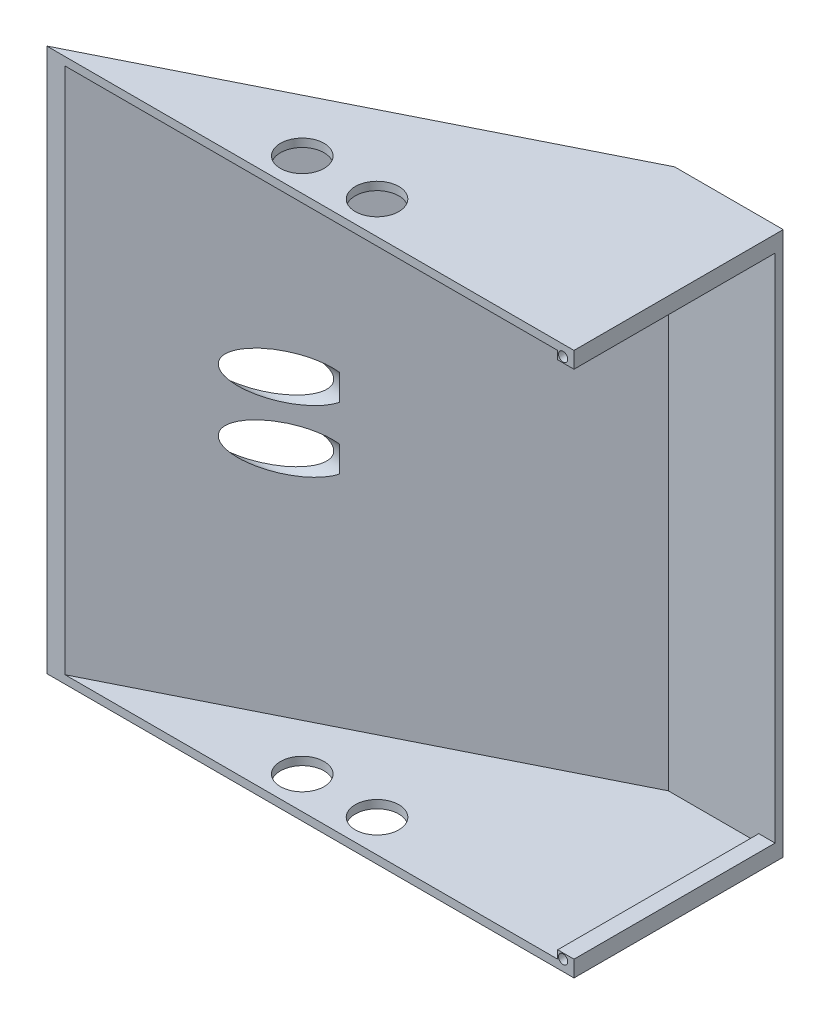
SolidWorks part; units mm, degrees
ref_plane "Alzado" through (0, 0, 0) normal (0, 0, 1) x (1, 0, 0)
ref_plane "Planta" through (0, 0, 0) normal (0, 1, 0) x (1, 0, 0)
ref_plane "Vista lateral" through (0, 0, 0) normal (1, 0, 0) x (0, 0, -1)
sketch "Croquis1" plane through (0, 0, 0) normal (0, 1, 0) x (1, 0, 0)
  line L0 (0, 0) -> (200, 0)
  line L5 (200, 0) -> (200, 80)
  line L6 (200, 80) -> (160, 80)
  line L7 (160, 80) -> (0, 0)
  dimension "D1" = 200
  dimension "D2" = 80
  dimension "D3" = 40
extrude "Saliente-Extruir2" add sketch "Croquis1" along normal blind 200
sketch "Croquis2" plane through (0, 200, 0) normal (0, 1, 0) x (1, 0, 0)
  line L0 (0, 0) -> (200, 0) construction
  circle A0 centre (88.0116, 15) radius 8.02
  circle A1 centre (115.5316, 15) radius 8.02
  dimension "D2" = 16.04
  dimension "D3" = 15
  dimension "D4" = 16.04
  dimension "D1" = 15
  dimension "D5" = 27.52
sketch "Croquis3" plane through (0, 0, -80) normal (0, 0, -1) x (-1, 0, 0)
  line L0 (-200, 0) -> (-200, 200) construction
sketch "Croquis5" plane through (0, 0, 0) normal (0, -1, 0) x (1, 0, 0)
  circle A0 centre (88.0116, -15) radius 8.02
  circle A1 centre (115.5316, -15) radius 8.02
ref_plane "Plano1" through (0, 0, 0) normal (1, 0, 0) x (0, 0, -1)
shell "Vaciado2" thickness 3
sketch "Croquis6" plane through (0, 0, 0) normal (1, 0, 0) x (0, 0, -1)
  line L1 (0, 200) -> (0, 0) construction
  line L3 (30, 88.575) -> (30, 111.425) construction
  line L4 (80, 0) -> (0, 0) construction
  circle A0 centre (30, 88.575) radius 8.2
  circle A1 centre (30, 111.425) radius 8.2
  point P2 (30, 100)
  dimension "D1" = 16.4
  dimension "D2" = 22.85
  dimension "D3" = 30
  dimension "D4" = 16.4
  dimension "D6" = 30
  dimension "D5" = 100
extrude "Cortar-Extruir4" cut sketch "Croquis6" along normal blind 80 contours A1 | A0
extrude "Cortar-Extruir5" cut sketch "Croquis2" against normal blind 3 contours A0 | A1
extrude "Cortar-Extruir6" cut sketch "Croquis5" against normal blind 3 contours A0 | A1
sketch "Croquis7" plane through (0, 0, 0) normal (0, 0, 1) x (1, 0, 0)
  line L0 (0, 0) -> (200, 0) construction
  line L1 (15, 10) -> (22.4, 10)
  line L2 (15, 10) -> (15, 17.4)
  line L3 (15, 17.4) -> (22.4, 17.4)
  line L4 (22.4, 10) -> (22.4, 17.4)
  line L5 (0, -44) -> (0, 44) construction
  point P4 (18.7, 10)
  dimension "D1" = 7.4
  dimension "D2" = 7.4
  dimension "D3" = 10
  dimension "D4" = 15
ref_plane "Plano2" through (0, 100, 0) normal (0, 1, 0) x (1, 0, 0)
extrude "Cortar-Extruir11" cut sketch "Croquis7" against normal blind 3 contours L4 L3 L2 L1
mirror "Simetría5" about plane through (0, 100, 0) normal (0, 1, 0) of "Cortar-Extruir11"
sketch "Croquis8" plane through (0, 0, 0) normal (0, 0, 1) x (1, 0, 0)
  line L0 (0, 200) -> (200, 200) construction
  line L1 (22.04, 103.52) -> (15, 103.52)
  line L2 (22.04, 103.52) -> (22.04, 96.48)
  line L3 (22.04, 96.48) -> (15, 96.48)
  line L4 (15, 103.52) -> (15, 96.48)
  line L5 (0, 0) -> (200, 0) construction
  line L7 (0, -44) -> (0, 44) construction
  point P6 (18.52, 103.52)
  point P9 (18.52, 96.48)
  dimension "D1" = 96.48
  dimension "D2" = 96.48
  dimension "D3" = 3.52
  dimension "D4" = 15
extrude "Cortar-Extruir12" cut sketch "Croquis8" against normal blind 3
sketch "Croquis9" plane through (0, 0, 0) normal (0, 0, 1) x (1, 0, 0)
  line L0 (200, 0) -> (200, 200) construction
  line L1 (192, 192) -> (157, 192)
  line L2 (192, 192) -> (192, 157)
  line L3 (192, 157) -> (157, 157)
  line L4 (157, 192) -> (157, 157)
  line L5 (0, 200) -> (200, 200) construction
  dimension "D1" = 8
  dimension "D2" = 8
  dimension "D3" = 35
  dimension "D4" = 35
extrude "Cortar-Extruir13" cut sketch "Croquis9" against normal blind 3
mirror "Simetría6" about plane through (0, 100, 0) normal (0, 1, 0) of "Cortar-Extruir13"
sketch "Croquis15" plane through (0, 0, -3) normal (0, 0, -1) x (-1, 0, 0)
  line L1 (-200, 3) -> (-194, 3)
  line L2 (-200, 3) -> (-200, 6)
  line L3 (-200, 6) -> (-194, 6)
  line L4 (-194, 3) -> (-194, 6)
  dimension "D1" = 6
  dimension "D2" = 3
extrude "Saliente-Extruir3" add sketch "Croquis15" along normal blind 75
mirror "Simetría7" about plane through (0, 100, 0) normal (0, 1, 0) of "Saliente-Extruir3"
sketch "Croquis16" plane through (0, 0, 0) normal (0, 0, 1) x (1, 0, 0)
  line L0 (0, 0) -> (200, 0) construction
  line L1 (200, 0) -> (200, 200) construction
  circle A0 centre (196, 4) radius 1.5
  dimension "D1" = 3
  dimension "D2" = 4
  dimension "D3" = 4
hole_wizard "Refrentado para tornillo tapón con cabeza plana de clavija de M33" positions "Croquis3D2" profile "Croquis18" countersink size "M3" standard "Ansi Metric"
sketch3d "Croquis3D2"
  point P0 (196, 4, 0)
sketch "Croquis18" plane through (196, 4, 0) normal (1, 0, 0) x (0, -1, 0)
  line L0 (0, 0) -> (0, 11.0215)
  line L1 (0, 11.0215) -> (1.7, 10)
  line L2 (1.7, 10) -> (1.7, 1.66)
  line L3 (1.7, 1.66) -> (3.36, 0)
  line L5 (3.36, 0) -> (0, 0)
  line L6 (-1.7, 1.66) -> (-3.36, 0) construction
  line L10 (0, 11.0215) -> (-1.7, 10) construction
  line L11 (0, -6.35) -> (0, 107.95) construction
  dimension "Diámetro de taladro" = 3.4
  dimension "Profundidad de taladro" = 10
  dimension "Ángulo de avellanado cercano" = 6.72
  dimension "Ángulo de avellanado lejano" = 90
  dimension "Ángulo de perforador" = 118
mirror "Simetría8" about plane through (0, 100, 0) normal (0, 1, 0) of "Refrentado para tornillo tapón con cabeza plana de clavija de M33"
ref_plane "Plano3" through (100, 0, 0) normal (1, 0, 0) x (0, 0, -1)
mirror "Simetría9" about plane through (100, 0, 0) normal (1, 0, 0) of "Simetría8", "Refrentado para tornillo tapón con cabeza plana de clavija de M33"
ref_plane "Plano4" through (0, 0, -3) normal (0, 0, 1) x (1, 0, 0)
split "Partir1" trim tools "Plano4" bodies to split 138 resulting bodies 139
